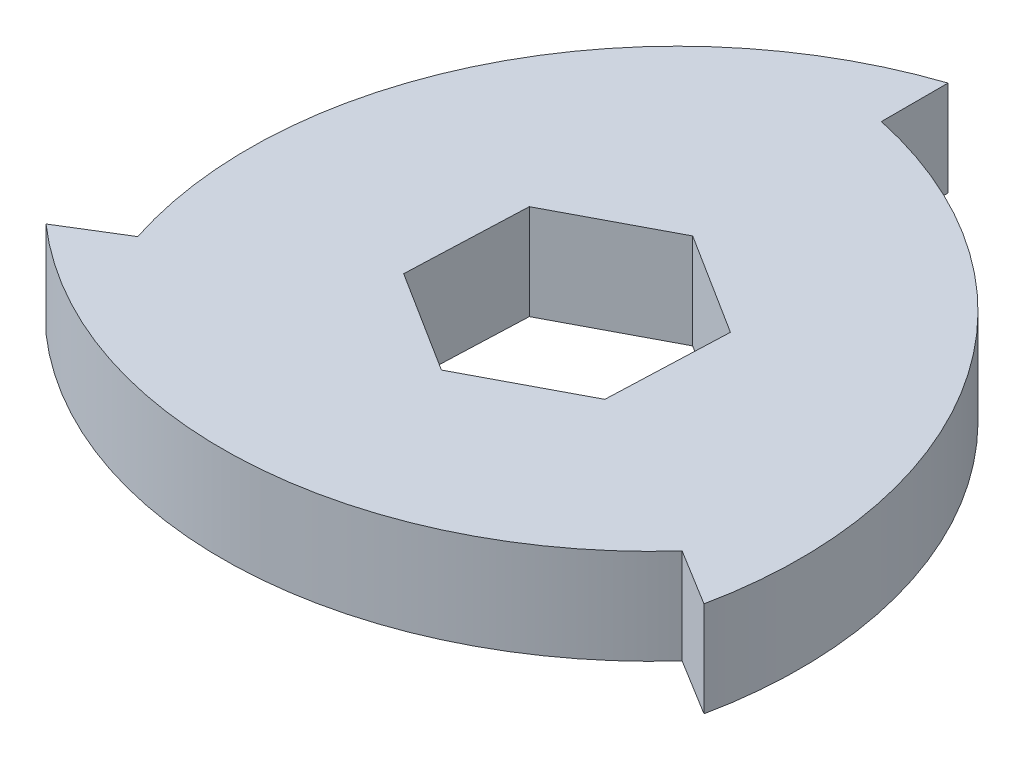
SolidWorks part; units mm, degrees
ref_plane "Ön Düzlem" through (0, 0, 0) normal (0, 0, 1) x (1, 0, 0)
ref_plane "Üst Düzlem" through (0, 0, 0) normal (0, 1, 0) x (1, 0, 0)
ref_plane "Sağ Düzlem" through (0, 0, 0) normal (1, 0, 0) x (0, 0, -1)
sketch "Sketch1" plane through (0, 0, 0) normal (0, 1, 0) x (1, 0, 0)
  circle A0 centre (0, 0) radius 40
  dimension "D1" = 80
extrude "Boss-Extrude1" add sketch "Sketch1" along normal blind 10
sketch "Sketch2" plane through (0, 10, 0) normal (0, 1, 0) x (1, 0, 0)
  line L0 (0, 50.6871) -> (0, -57.7028) construction
  line L1 (68.1824, 0) -> (-68.1875, 0) construction
  line L2 (0, -40) -> (0, -34)
  line L3 (0.4971, 12.6919) -> (-10.7442, 6.7787)
  line L4 (-10.7442, 6.7787) -> (-11.2439, -5.9132)
  line L5 (-11.2439, -5.9132) -> (-0.5022, -12.6919)
  line L6 (-0.5022, -12.6919) -> (10.7391, -6.7787)
  line L7 (10.7391, -6.7787) -> (11.2388, 5.9132)
  line L8 (11.2388, 5.9132) -> (0.4971, 12.6919)
  line L9 (0, 40) -> (0, 33) construction
  line L10 (0, 33) -> (-28.5801, -16.5022) construction
  line L11 (-0.0025, 0) -> (70.3241, -40.6031) construction
  line L12 (9.525, 5.4978) -> (-69.0473, -39.8659) construction
  line L13 (-28.5801, -16.5022) -> (28.5801, -16.5022) construction
  line L14 (28.5801, -16.5022) -> (0, 33) construction
  line L15 (28.5801, -16.5022) -> (34.5432, -20.1684)
  line L16 (-28.5801, -16.5022) -> (-34.5432, -20.1684)
  line L17 (0, 40) -> (0, 33)
  circle A0 centre (-0.0025, 0) radius 11 construction
  arc A1 (-28.5801, -16.5022) -> (0, 40) centre (14.2462, -2.6854) cw
  circle A2 centre (0, 0) radius 40 construction
  arc A3 (0, 33) -> (34.5432, -20.1684) centre (-9.5095, -10.9837) cw
  arc A4 (28.5801, -16.5022) -> (-34.5432, -20.1684) centre (-4.8384, 13.6343) cw
  point P5 (-34.5432, -20.1684)
  point P13 (34.5432, -20.1684)
  point P22 (-28.5801, -16.5022)
  point P23 (28.5801, -16.5022)
  dimension "D1" = 22
  dimension "D4" = 7
  dimension "D3" = 7
  dimension "D5" = 57.1602
  dimension "D6" = 30
  dimension "D7" = 30
  dimension "D10" = 45
  dimension "D11" = 45
  dimension "D12" = 45
  dimension "D2" = 7
  dimension "D8" = 30
  dimension "D9" = 30
extrude "Cut-Extrude1" cut sketch "Sketch2" against normal up to next
